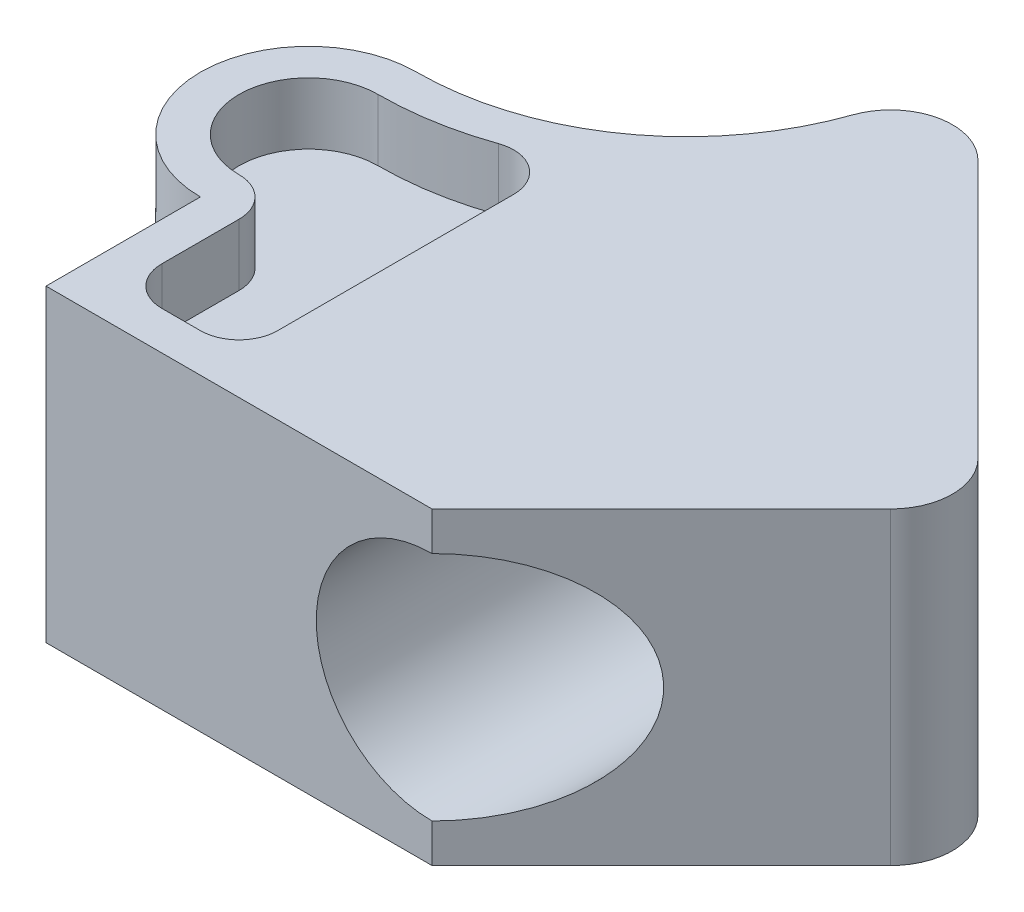
SolidWorks part; units mm, degrees
material "1060 Alloy"
ref_plane "Front Plane" through (0, 0, 0) normal (0, 0, 1) x (1, 0, 0)
ref_plane "Top Plane" through (0, 0, 0) normal (0, 1, 0) x (1, 0, 0)
ref_plane "Right Plane" through (0, 0, 0) normal (1, 0, 0) x (0, 0, -1)
sketch "Sketch1" plane through (0, 0, 0) normal (0, 1, 0) x (1, 0, 0)
  line L0 (0, 0) -> (50, 0)
  line L1 (50, 0) -> (79.6985, 29.6985)
  line L2 (79.6985, 41.0122) -> (46.2469, 74.4637)
  line L3 (0, 0) -> (0, 20)
  line L4 (-80.8464, 34) -> (138.1304, 34) construction
  line L7 (0, 120.0502) -> (0, -87.3472) construction
  arc A1 (46.2469, 74.4637) -> (33.0384, 71.4475) centre (40.5901, 68.8069) ccw
  arc A2 (33.0384, 71.4475) -> (0, 48) centre (0, 83) cw
  arc A3 (0, 48) -> (0, 20) centre (0, 34) ccw
  arc A4 (79.6985, 29.6985) -> (79.6985, 41.0122) centre (74.0416, 35.3553) ccw
  point P7 (85.3553, 48)
  point P15 (0, 83)
  point P16 (85.3553, 42.0131)
  point P17 (0, 0)
  point P20 (0, 20)
  point P21 (0, 48)
  point P22 (0, 0)
  point P23 (50, 80.5988)
  point P24 (114.3551, 5.5952)
  point P25 (121.3192, 5.4178)
  point P27 (85.3553, 35.3553)
  point P28 (43.8661, 70.381)
  point P29 (0, 0)
  dimension "D4" = 14
  dimension "D5" = 35
  dimension "D8" = 8
  dimension "D1" = 50
  dimension "D3" = 20
  dimension "D7" = 135
  dimension "D2" = 50
extrude "Boss-Extrude1" add sketch "Sketch1" along normal blind 40
sketch "Sketch2" plane through (0, 40, 0) normal (0, 1, 0) x (1, 0, 0)
  line L4 (20, 10) -> (20, 40.5736)
  line L8 (5, 26.5167) -> (5, 5)
  line L9 (5, 5) -> (47.9289, 5)
  line L10 (47.9289, 5) -> (76.163, 33.234)
  line L11 (76.163, 37.4767) -> (42.7114, 70.9282)
  line L12 (5, 20) -> (5, 10)
  line L13 (10, 5) -> (15, 5)
  arc A4 (10, 5) -> (5, 10) centre (10, 10) cw
  arc A5 (15, 5) -> (20, 10) centre (15, 10) ccw
  arc A6 (20, 40.5736) -> (13.3333, 45.2876) centre (15, 40.5736) ccw
  arc A7 (5, 20) -> (0, 25) centre (0, 20) ccw
  arc A8 (76.163, 33.234) -> (76.163, 37.4767) centre (74.0416, 35.3553) ccw
  arc A9 (42.7114, 70.9282) -> (37.7582, 69.7971) centre (40.5901, 68.8069) ccw
  arc A10 (0, 43) -> (37.7582, 69.7971) centre (0, 83) ccw
  arc A11 (0, 43) -> (5, 26.5167) centre (0, 34) ccw
  arc A14 (0, 43) -> (13.3333, 45.2876) centre (0, 83) ccw
  arc A15 (0, 43) -> (0, 25) centre (0, 34) ccw
  dimension "D3" = 5
  dimension "D2" = 15
  dimension "D1" = 5
extrude "Cut-Extrude1" cut sketch "Sketch2" against normal blind 8
sketch "Sketch3" plane through (0, 0, 0) normal (0, 0, 1) x (1, 0, 0)
  line L0 (-38.3052, 20) -> (111.7242, 20) construction
  line L1 (50, -42.1089) -> (50, 75.6561) construction
  line L2 (0, 0) -> (50, 0) construction
  line L3 (-14, 40) -> (-14, 0) construction
  line L5 (-14, 28) -> (-14, 12)
  circle A0 centre (50, 20) radius 15
  arc A1 (-14, 28) -> (-14, 12) centre (-14, 20) cw
  point P12 (-14, 35.7289)
  point P14 (0, 0)
  dimension "D3" = 30
  dimension "D4" = 8
  dimension "D1" = 20
  dimension "D2" = 64
extrude "Cut-Extrude2" cut sketch "Sketch3" against normal through all both and the other way through all
equation "\"A\"= 50"
equation "\"B\"= 10"
equation "\"C\"= \"B\" + 20"
equation "\"D1@Sketch1\"=\"A\""
equation "\"D3@Sketch3\"=\"C\""
equation "\"D2@Sketch1\"=\"A\""
